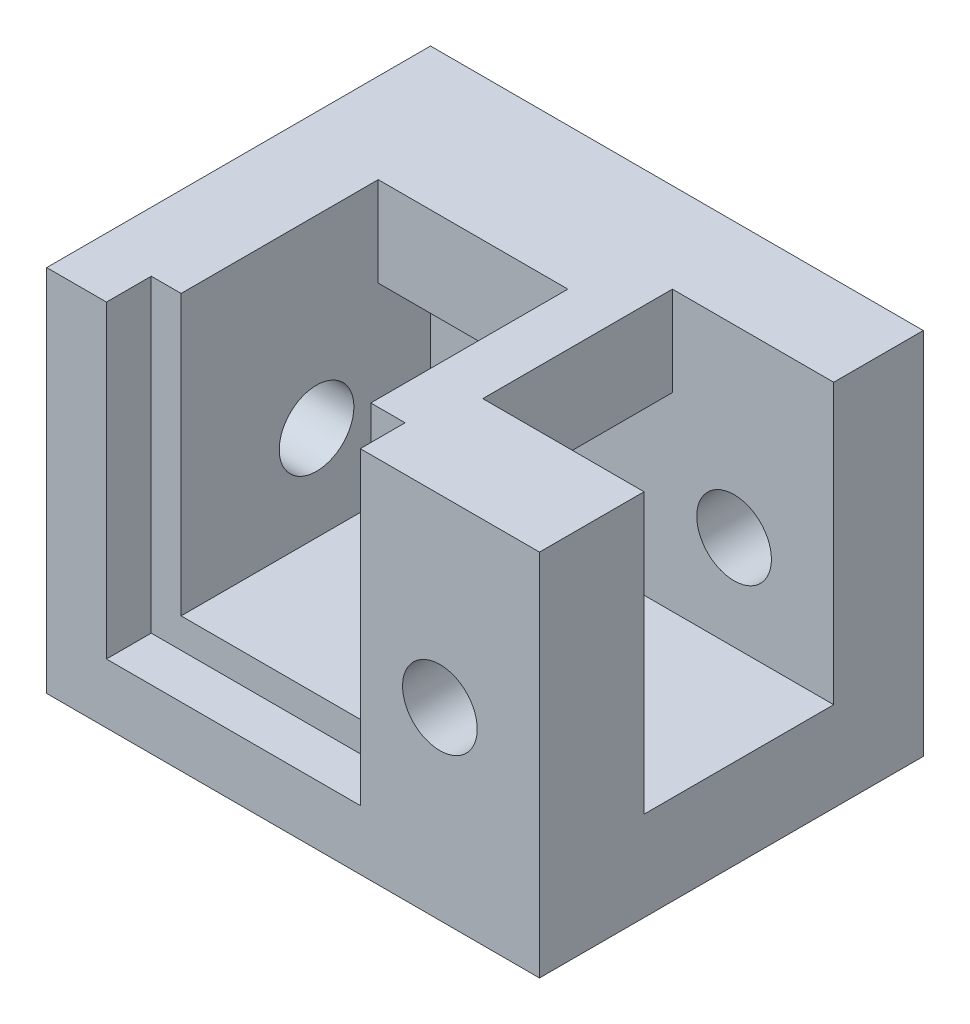
SolidWorks part; units mm, degrees
ref_plane "前视基准面" through (0, 0, 0) normal (0, 0, 1) x (1, 0, 0)
ref_plane "上视基准面" through (0, 0, 0) normal (0, 1, 0) x (1, 0, 0)
ref_plane "右视基准面" through (0, 0, 0) normal (1, 0, 0) x (0, 0, -1)
sketch "草图3" plane through (0, 0, 0) normal (0, 1, 0) x (1, 0, 0)
  line L1 (0, 0) -> (33, 0)
  line L2 (0, 0) -> (0, 22.7)
  line L3 (0, 22.7) -> (33, 22.7)
  line L4 (33, 0) -> (33, 22.7)
  dimension "D1" = 22.7
  dimension "D2" = 33
extrude "凸台-拉伸2" add sketch "草图3" along normal blind 6
sketch "草图4" plane through (0, 6, 0) normal (0, 1, 0) x (1, 0, 0)
  line L0 (33, 0) -> (18.7, 0)
  line L1 (0, 0) -> (33, 0) construction
  line L2 (18.7, 0) -> (18.7, 4)
  line L3 (18.7, 4) -> (33, 4)
  line L4 (33, 0) -> (33, 22.7) construction
  line L5 (33, 4) -> (33, 0)
  line L6 (0, 0) -> (6, 0)
  line L7 (6, 0) -> (6, 16.7)
  line L8 (6, 16.7) -> (33, 16.7)
  line L9 (33, 16.7) -> (33, 22.7)
  line L10 (33, 22.7) -> (0, 22.7)
  line L11 (0, 22.7) -> (0, 0)
  dimension "D1" = 4
  dimension "D2" = 6
  dimension "D3" = 6
  dimension "D4" = 14.3
extrude "凸台-拉伸3" add sketch "草图4" along normal blind 12.7
sketch "草图5" plane through (0, 0, 0) normal (0, 0, 1) x (1, 0, 0)
  line L0 (18.7, 18.7) -> (33, 18.7) construction
  line L1 (18.7, 18.7) -> (18.7, 6) construction
  circle A0 centre (26.33, 12.35) radius 2.5
  dimension "D1" = 5
  dimension "D2" = 6.35
  dimension "D3" = 7.63
extrude "切除-拉伸2" cut sketch "草图5" against normal through all
sketch "草图6" plane through (6, 0, 0) normal (1, 0, 0) x (0, 0, -1)
  line L3 (0, 6) -> (16.7, 6) construction
  line L4 (16.7, 18.7) -> (16.7, 6) construction
  circle A0 centre (9.07, 12.35) radius 2.5
  dimension "D3" = 5
  dimension "D1" = 7.63
  dimension "D2" = 6.35
extrude "切除-拉伸3" cut sketch "草图6" against normal through all
sketch "草图7" plane through (0, 18.7, 0) normal (0, 1, 0) x (1, 0, 0)
  line L0 (0, 0) -> (0, 22.7)
  line L1 (0, 22.7) -> (18.7, 22.7)
  line L2 (33, 22.7) -> (0, 22.7) construction
  line L3 (18.7, 22.7) -> (18.7, 4)
  line L4 (18.7, 4) -> (18.7, 0)
  line L5 (18.7, 0) -> (33, 0)
  line L6 (33, 0) -> (33, 4)
  line L7 (33, 4) -> (22.2, 4)
  line L8 (33, 4) -> (18.7, 4) construction
  line L9 (22.2, 4) -> (22.2, 16.7)
  line L10 (6, 16.7) -> (33, 16.7) construction
  line L11 (22.2, 16.7) -> (33, 16.7)
  line L12 (33, 16.7) -> (33, 22.7)
  line L13 (33, 22.7) -> (18.7, 22.7)
  line L14 (0, 0) -> (6, 0)
  line L15 (6, 0) -> (6, 13.2)
  line L16 (6, 0) -> (6, 16.7) construction
  line L17 (6, 13.2) -> (18.7, 13.2)
  line L18 (18.7, 13.2) -> (18.7, 22.7)
  line M16 (0, 22.7) -> (0, 0)
  line M17 (0, 0) -> (6, 0)
  line M18 (6, 0) -> (6, 16.7)
  line M19 (6, 16.7) -> (33, 16.7)
  line M20 (33, 16.7) -> (33, 22.7)
  line M21 (33, 22.7) -> (0, 22.7)
  dimension "D1" = 3.5
  dimension "D2" = 3.5
extrude "凸台-拉伸4" add sketch "草图7" along normal blind 6 contours L3 M21 M16 M17 M18 M19 | L3 M21 M19 M20 | L7 L9 L3 L4 L5 L6 M19 | L17 L3 M18 M19
sketch "草图8" plane through (0, 0, 0) normal (0, 0, 1) x (1, 0, 0)
  line L0 (0, 0) -> (33, 0) construction
  line L1 (33, 24.7) -> (21, 24.7)
  line L2 (33, 24.7) -> (33, 0)
  line L3 (33, 0) -> (21, 0)
  line L4 (21, 24.7) -> (21, 0)
  circle A0 centre (26.33, 12.35) radius 2.5
  dimension "D2" = 5
  dimension "D1" = 12
extrude "凸台-拉伸5" add sketch "草图8" along normal blind 3
sketch "草图9" plane through (0, 0, 0) normal (0, 0, 1) x (1, 0, 0)
  line L0 (0, 24.7) -> (0, 0)
  line L1 (0, 0) -> (21, 0)
  line L2 (21, 0) -> (21, 4)
  line L3 (21, 24.7) -> (21, 0) construction
  line L4 (21, 4) -> (4, 4)
  line L5 (4, 4) -> (4, 24.7)
  line L6 (0, 24.7) -> (6, 24.7) construction
  line L7 (4, 24.7) -> (0, 24.7)
  dimension "D1" = 4
  dimension "D2" = 4
extrude "凸台-拉伸6" add sketch "草图9" along normal blind 3
